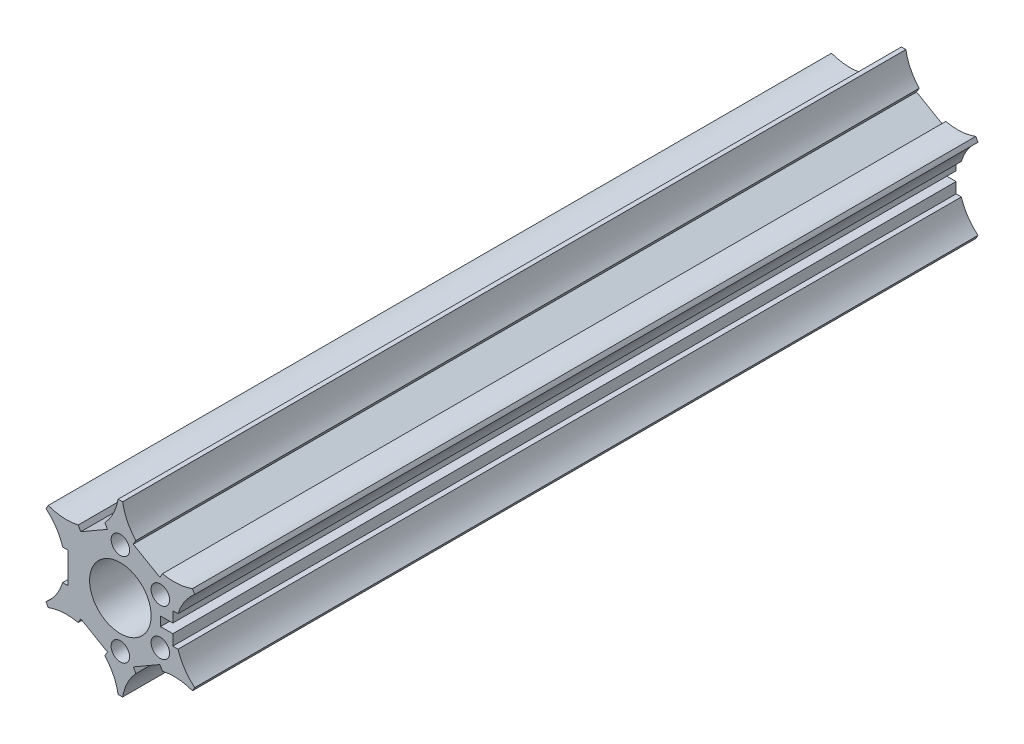
SolidWorks part; units mm, degrees
ref_plane "Plan de face" through (0, 0, 0) normal (0, 0, 1) x (1, 0, 0)
ref_plane "Plan de dessus" through (0, 0, 0) normal (0, 1, 0) x (1, 0, 0)
ref_plane "Plan de droite" through (0, 0, 0) normal (1, 0, 0) x (0, 0, -1)
sketch "Esquisse1" plane through (0, 0, 0) normal (0, 0, 1) x (1, 0, 0)
  line L0 (-35, 0) -> (35, 0) construction
  line L2 (0, 0) -> (0, -53.5) construction
  line L4 (-31.4635, 18.3063) -> (31.5363, 18.1806) construction
  line L5 (-31.4635, 18.3063) -> (-31.4137, 43.3063) construction
  line L6 (-31.4137, 43.3063) -> (31.5862, 43.1806) construction
  line L7 (31.5363, 18.1806) -> (31.5862, 43.1806) construction
  line L8 (-49.7224, 8.5) -> (-35, 0) construction
  line L9 (-35, 0) -> (-49.7224, -8.5) construction
  line L12 (-17.5, -48.3109) -> (-17.5, -47.3109)
  line L17 (-34.6353, -19.9967) -> (0, 0) construction
  line L19 (-49.7224, 8.5) -> (-50.5885, 9)
  line L20 (-32.2224, 38.8109) -> (-33.0885, 39.3109)
  line L21 (-17.5, 48.3109) -> (-17.5, 47.3109)
  line L23 (-49.7224, -8.5) -> (-50.5885, -9)
  line L25 (-32.2224, -38.8109) -> (-33.0885, -39.3109)
  line L26 (49.7224, -8.5) -> (50.5885, -9)
  line L27 (32.2224, -38.8109) -> (33.0885, -39.3109)
  line L28 (17.5, -48.3109) -> (17.5, -47.3109)
  line L30 (17.5, 48.3109) -> (17.5, 47.3109)
  line L31 (32.2224, 38.8109) -> (33.0885, 39.3109)
  line L32 (49.7224, 8.5) -> (50.5885, 9)
  circle A0 centre (0, 0) radius 17.5 construction
  circle A1 centre (35, 0) radius 17.5 construction
  circle A2 centre (-35, 0) radius 17.5 construction
  circle A3 centre (-17.5, -30.3109) radius 17.5 construction
  circle A4 centre (17.5, -30.3109) radius 17.5 construction
  circle A6 centre (0, 0) radius 53.5 construction
  circle A7 centre (0, 0) radius 17 construction
  circle A8 centre (35, 0) radius 17 construction
  circle A11 centre (17.5, -30.3109) radius 17 construction
  arc A12 (-49.7224, 8.5) -> (-49.7224, -8.5) centre (-35, 0) cw
  circle A24 centre (-35, 0) radius 18 construction
  arc A25 (-50.5885, -9) -> (-29.8986, -17.262) centre (-35, 0) ccw
  arc A26 (-17.5, -47.3109) -> (-32.2224, -38.8109) centre (-17.5, -30.3109) ccw
  arc A27 (-33.0885, -39.3109) -> (-29.8986, -17.262) centre (-17.5, -30.3109) cw
  arc A29 (-17.5, -48.3109) -> (0, -34.524) centre (-17.5, -30.3109) ccw
  arc A32 (50.5885, -9) -> (29.8986, -17.262) centre (35, 0) cw
  arc A33 (33.0885, -39.3109) -> (29.8986, -17.262) centre (17.5, -30.3109) ccw
  arc A34 (17.5, -47.3109) -> (32.2224, -38.8109) centre (17.5, -30.3109) cw
  arc A35 (17.5, -48.3109) -> (0, -34.524) centre (17.5, -30.3109) cw
  arc A36 (-50.5885, 9) -> (-29.8986, 17.262) centre (-35, 0) cw
  arc A37 (-33.0885, 39.3109) -> (-29.8986, 17.262) centre (-17.5, 30.3109) ccw
  arc A38 (-17.5, 47.3109) -> (-32.2224, 38.8109) centre (-17.5, 30.3109) cw
  arc A39 (-17.5, 48.3109) -> (0, 34.524) centre (-17.5, 30.3109) cw
  arc A40 (17.5, 48.3109) -> (0, 34.524) centre (17.5, 30.3109) ccw
  arc A41 (17.5, 47.3109) -> (32.2224, 38.8109) centre (17.5, 30.3109) ccw
  arc A42 (33.0885, 39.3109) -> (29.8986, 17.262) centre (17.5, 30.3109) cw
  arc A43 (50.5885, 9) -> (29.8986, 17.262) centre (35, 0) ccw
  arc A44 (49.7224, -8.5) -> (49.7224, 8.5) centre (35, 0) cw
  point P48 (0, 0)
  point P61 (0, 0)
  point P69 (0, 0)
  dimension "D1" = 35
  dimension "D2" = 1
  dimension "D5" = 17
  dimension "D6" = 17
  dimension "D7" = 60
  dimension "D8" = 35
  dimension "D9" = 20
  dimension "D10" = 1
  dimension "D11" = 2
  dimension "D13" = 107
  dimension "D3" = 63
  dimension "D4" = 25
extrude "Boss.-Extru.1" add sketch "Esquisse1" along normal blind 254.6667
sketch "Esquisse4" plane through (0, 0, 254.6667) normal (0, 0, 1) x (1, 0, 0)
  circle A3 centre (0, 0) radius 27.5
  circle A5 centre (0, 0) radius 51.3828
  point P2 (19.1906, 6.25)
  point P4 (0, 0)
  dimension "D1" = 55
extrude "Enlèv. mat.-Extru.1" cut sketch "Esquisse4" against normal through all
sketch "Esquisse5" plane through (0, 0, 254.6667) normal (0, 0, 1) x (1, 0, 0)
  line L0 (13.7061, -13.7396) -> (5.0458, -18.7396)
  line L1 (17.0519, 5) -> (18.7519, 5)
  line L2 (17.0519, 5) -> (17.0519, -5) construction
  line L3 (17.0519, -5) -> (18.7519, -5)
  line L4 (18.7519, 5) -> (18.7519, -5)
  line L5 (4.1958, -17.2674) -> (5.0458, -18.7396)
  line L6 (12.8561, -12.2674) -> (4.1958, -17.2674)
  line L7 (12.8561, -12.2674) -> (13.7061, -13.7396)
  line L8 (-5.0458, -18.7396) -> (-13.7061, -13.7396)
  line L9 (-12.8561, -12.2674) -> (-13.7061, -13.7396)
  line L10 (-4.1958, -17.2674) -> (-12.8561, -12.2674)
  line L11 (-4.1958, -17.2674) -> (-5.0458, -18.7396)
  line L12 (-18.7519, -5) -> (-18.7519, 5)
  line L13 (-17.0519, 5) -> (-18.7519, 5)
  line L14 (-17.0519, -5) -> (-17.0519, 5)
  line L15 (-17.0519, -5) -> (-18.7519, -5)
  line L16 (-13.7061, 13.7396) -> (-5.0458, 18.7396)
  line L17 (-4.1958, 17.2674) -> (-5.0458, 18.7396)
  line L18 (-12.8561, 12.2674) -> (-4.1958, 17.2674)
  line L19 (-12.8561, 12.2674) -> (-13.7061, 13.7396)
  line L20 (5.0458, 18.7396) -> (13.7061, 13.7396)
  line L21 (12.8561, 12.2674) -> (13.7061, 13.7396)
  line L22 (4.1958, 17.2674) -> (12.8561, 12.2674)
  line L23 (4.1958, 17.2674) -> (5.0458, 18.7396)
  line L24 (0, 15) -> (0, 0) construction
  line L25 (17.0519, 5) -> (17.0519, 1.5)
  line L26 (17.0519, 1.5) -> (13.0519, 1.5)
  line L27 (13.0519, 1.5) -> (13.0519, -1.5)
  line L28 (13.0519, -1.5) -> (17.0519, -1.5)
  line L29 (17.0519, -1.5) -> (17.0519, -5)
  line L30 (0, 0) -> (17.0519, 0) construction
  arc A0 (24.175, 13.108) -> (24.175, -13.108) centre (35, 0) ccw construction
  circle A1 centre (0, 0) radius 10
  circle A2 centre (0, 15) radius 3
  circle A3 centre (12.9904, 7.5) radius 3
  circle A4 centre (12.9904, -7.5) radius 3
  circle A5 centre (0, -15) radius 3
  point P29 (0, 0)
  point P33 (0, 0)
  point P42 (0, 0)
  dimension "D3" = 20
  dimension "D4" = 6
  dimension "D6" = 4
  dimension "D1" = 1.7
  dimension "D2" = 10
  dimension "D5" = 15
  dimension "D7" = 6
  dimension "D8" = 3
  dimension "D9" = 3
  dimension "D10" = 4
extrude "Enlèv. mat.-Extru.2" cut sketch "Esquisse5" against normal through all
